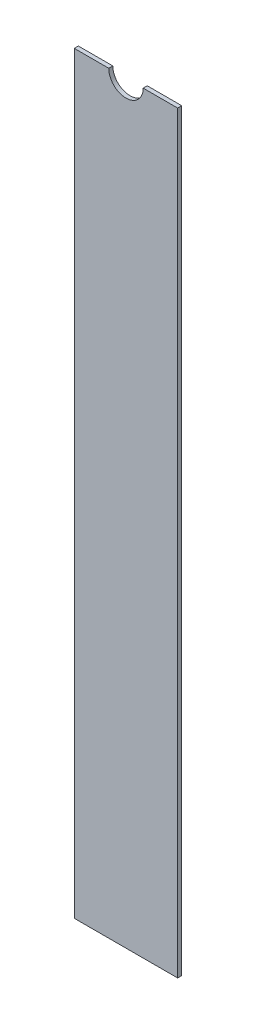
SolidWorks part; units mm, degrees
ref_plane "Front Plane" through (0, 0, 0) normal (0, 0, 1) x (1, 0, 0)
ref_plane "Top Plane" through (0, 0, 0) normal (0, 1, 0) x (1, 0, 0)
ref_plane "Right Plane" through (0, 0, 0) normal (1, 0, 0) x (0, 0, -1)
sketch "Sketch1" plane through (0, 0, 0) normal (0, 0, 1) x (1, 0, 0)
  line L0 (38.1, 0) -> (-38.1, 0)
  line L1 (38.1, 0) -> (38.1, 584.2)
  line L2 (38.1, 584.2) -> (-38.1, 584.2)
  line L3 (-38.1, 584.2) -> (-38.1, 0)
  line L4 (0, 584.2) -> (0, 0) construction
  circle A1 centre (0, 555.4228) radius 12.7
  point P1 (0, 0)
  point P7 (0, 0)
  dimension "D4" = 25.4
  dimension "D1" = 584.2
  dimension "D2" = 76.2
  dimension "D3" = 555.4228
extrude "Boss-Extrude1" add sketch "Sketch1" along normal blind 3
sketch "Sketch2" plane through (0, 0, 3) normal (0, 0, 1) x (1, 0, 0)
  line L0 (-38.1, 584.2) -> (-38.1, 555.4228)
  line L1 (-38.1, 584.2) -> (-38.1, 0) construction
  line L2 (-38.1, 555.4228) -> (38.1, 555.4228)
  line L3 (38.1, 0) -> (38.1, 584.2) construction
  line L4 (38.1, 555.4228) -> (38.1, 584.2)
  line L5 (38.1, 584.2) -> (-38.1, 584.2)
  line L6 (-12.7, 555.4228) -> (12.7, 555.4228) construction
  circle A0 centre (0, 555.4228) radius 12.7 construction
  circle A1 centre (0, 555.4228) radius 12.7 construction
extrude "Cut Out" cut sketch "Sketch2" against normal through all
